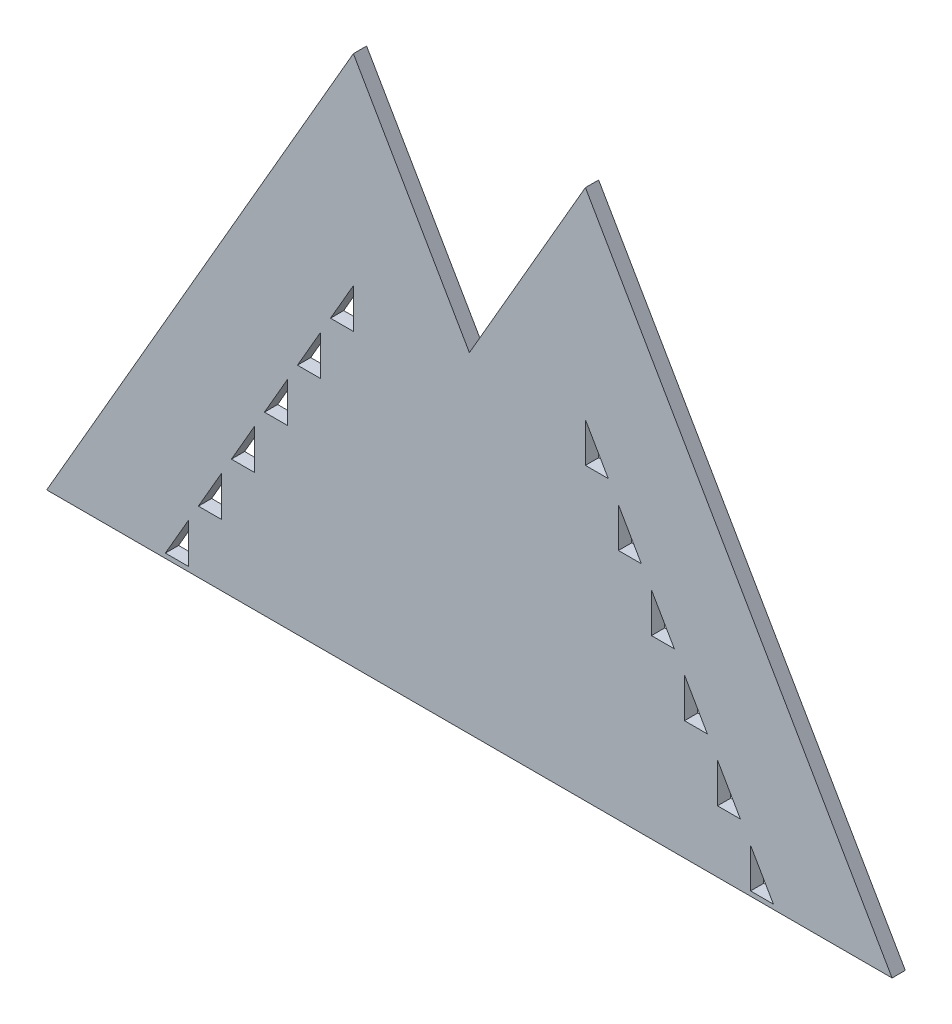
SolidWorks part; units mm, degrees
ref_plane "前视基准面" through (0, 0, 0) normal (0, 0, 1) x (1, 0, 0)
ref_plane "上视基准面" through (0, 0, 0) normal (0, 1, 0) x (1, 0, 0)
ref_plane "右视基准面" through (0, 0, 0) normal (1, 0, 0) x (0, 0, -1)
sketch "草图1" plane through (0, 0, 0) normal (0, 0, 1) x (1, 0, 0)
  line L0 (-32, 0) -> (32, 0)
  line L1 (-32, 0) -> (0, 55.4256) construction
  line L2 (0, 55.4256) -> (32, 0) construction
  line L3 (-54.92, 25) -> (63.5506, 25) construction
  line L4 (0, 55.4256) -> (0, 25) construction
  line L5 (-21.0105, 40.2128) -> (25.9522, 40.2128) construction
  line L6 (-8.7831, 40.2128) -> (0, 25)
  line L7 (0, 25) -> (8.7831, 40.2128)
  line L8 (-8.7831, 40.2128) -> (-32, 0)
  line L9 (8.7831, 40.2128) -> (32, 0)
  point P9 (0, 40.2128)
  dimension "D1" = 64
  dimension "D2" = 32
  dimension "D3" = 60
  dimension "D4" = 25
extrude "凸台-拉伸1" add sketch "草图1" along normal blind 1
sketch "草图2" plane through (0, 0, 1) normal (0, 0, 1) x (1, 0, 0)
  line L0 (-4.3916, 32.6064) -> (-23.7926, -0.9972) construction
  line L1 (0, 25) -> (-8.7831, 40.2128) construction
  line L2 (-8.7831, 40.2128) -> (-32, 0) construction
  line L3 (0, 25) -> (-27.0373, 25) construction
  line L4 (-8.7831, 25) -> (-10.5152, 22)
  line L5 (-10.5152, 22) -> (-8.7831, 22)
  line L6 (-8.7831, 22) -> (-8.7831, 25)
  line L7 (-11.2831, 17.6699) -> (-11.2831, 20.6699)
  line L8 (-11.2831, 20.6699) -> (-13.0152, 17.6699)
  line L9 (-13.0152, 17.6699) -> (-11.2831, 17.6699)
  line L10 (-13.7831, 13.3397) -> (-13.7831, 16.3397)
  line L11 (-13.7831, 16.3397) -> (-15.5152, 13.3397)
  line L12 (-15.5152, 13.3397) -> (-13.7831, 13.3397)
  line L13 (-16.2831, 9.0096) -> (-16.2831, 12.0096)
  line L14 (-16.2831, 12.0096) -> (-18.0152, 9.0096)
  line L15 (-18.0152, 9.0096) -> (-16.2831, 9.0096)
  line L16 (-18.7831, 4.6795) -> (-18.7831, 7.6795)
  line L17 (-18.7831, 7.6795) -> (-20.5152, 4.6795)
  line L18 (-20.5152, 4.6795) -> (-18.7831, 4.6795)
  line L19 (-21.2831, 0.3494) -> (-21.2831, 3.3494)
  line L20 (-21.2831, 3.3494) -> (-23.0152, 0.3494)
  line L21 (-23.0152, 0.3494) -> (-21.2831, 0.3494)
  line L22 (-8.7831, 22) -> (-11.2831, 17.6699) construction
  line L23 (0, -0.55) -> (0, 0.55) construction
  line L24 (23.0152, 0.3494) -> (21.2831, 0.3494)
  line L25 (21.2831, 3.3494) -> (23.0152, 0.3494)
  line L26 (21.2831, 0.3494) -> (21.2831, 3.3494)
  line L27 (20.5152, 4.6795) -> (18.7831, 4.6795)
  line L28 (18.7831, 7.6795) -> (20.5152, 4.6795)
  line L29 (18.7831, 4.6795) -> (18.7831, 7.6795)
  line L30 (18.0152, 9.0096) -> (16.2831, 9.0096)
  line L31 (16.2831, 12.0096) -> (18.0152, 9.0096)
  line L32 (16.2831, 9.0096) -> (16.2831, 12.0096)
  line L33 (15.5152, 13.3397) -> (13.7831, 13.3397)
  line L34 (13.7831, 16.3397) -> (15.5152, 13.3397)
  line L35 (13.7831, 13.3397) -> (13.7831, 16.3397)
  line L36 (13.0152, 17.6699) -> (11.2831, 17.6699)
  line L37 (11.2831, 20.6699) -> (13.0152, 17.6699)
  line L38 (11.2831, 17.6699) -> (11.2831, 20.6699)
  line L39 (10.5152, 22) -> (8.7831, 22)
  line L40 (8.7831, 25) -> (10.5152, 22)
  line L41 (8.7831, 22) -> (8.7831, 25)
  dimension "D1" = 3
  dimension "D3" = 5
  dimension "D2" = 6
extrude "切除-拉伸1" cut sketch "草图2" against normal through all
